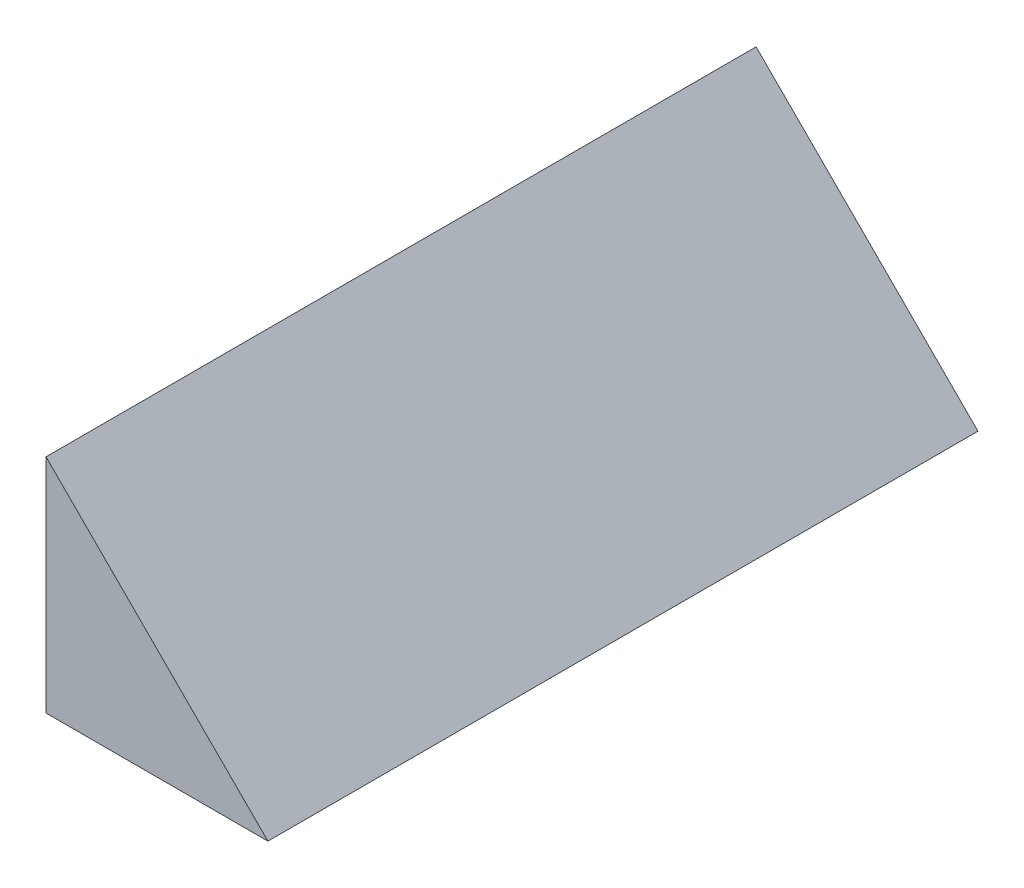
SolidWorks part; units mm, degrees
ref_plane "Front Plane" through (0, 0, 0) normal (0, 0, 1) x (1, 0, 0)
ref_plane "Top Plane" through (0, 0, 0) normal (0, 1, 0) x (1, 0, 0)
ref_plane "Right Plane" through (0, 0, 0) normal (1, 0, 0) x (0, 0, -1)
sketch "Sketch1" plane through (0, 0, 0) normal (0, 0, 1) x (1, 0, 0)
  line L0 (0, 0) -> (0, 0.25)
  line L1 (0, 0) -> (0.25, 0)
  line L5 (0, 0.25) -> (0.25, 0)
  dimension "D1" = 0.25
  dimension "D2" = 0.25
extrude "Boss-Extrude1" add sketch "Sketch1" along normal blind 0.8
equation "\"t\"= 0.25'thickness of the sheets"
equation "\"t_cf\"= 0.115'thickness of single carbon fiber layer"
equation "\"t_kapton\"= 0.025'thickness of single Kapton flex layer"
equation "\"t_fr4\"= 0.1'thickness of FR4 with copper layer"
equation "\"joint_flex\"= 0.1'Width of flextures gap"
equation "\"joint_flex_eff\"= 0.02'Width of flecture after castelation"
equation "\"joint_fold\"= 0.2'Width of folding joints for 90deg fold"
equation "\"gap_tolerance\"= 0.002'Width to have interfecence fit between carbon fiber inserts"
equation "\"assemble_angle\"= 90'Angle of assembly parts"
equation "\"link_lift\"= 0.5'Actuation linkage amplification for the lift motion"
equation "\"link_swing\"= 0.45'Actuation linkage amplification for the swing motion"
equation "\"D1@Boss-Extrude1\"=\"joint_fold\""
equation "\"D1@Sketch1\"=\"t\""
equation "\"D2@Sketch1\"=\"t\""
